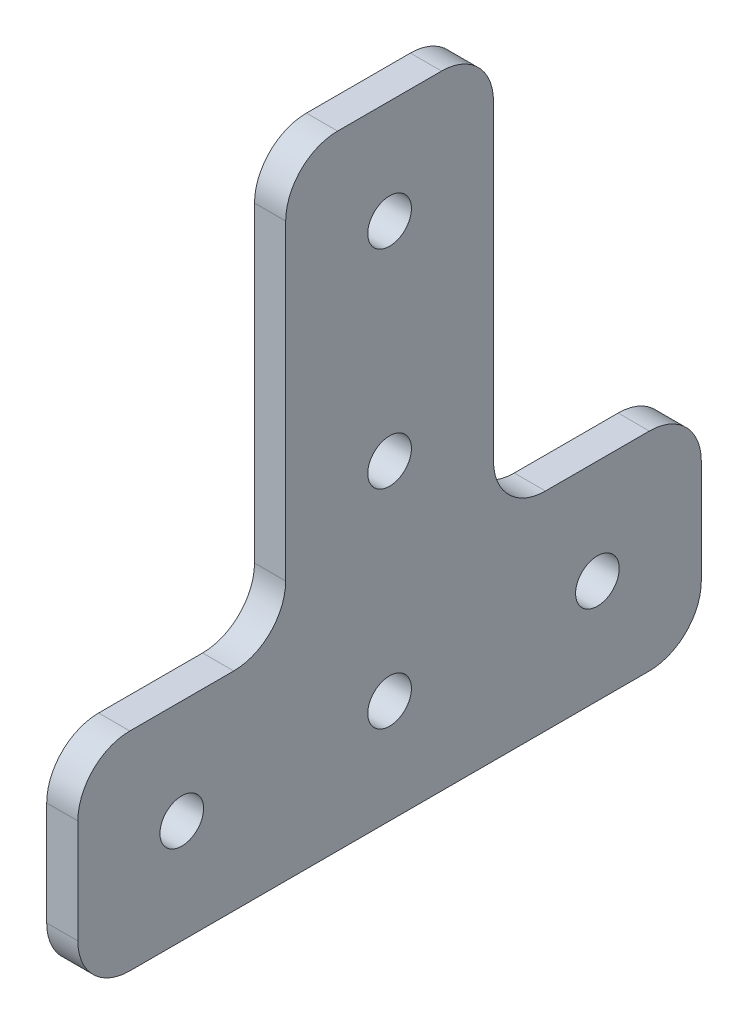
SolidWorks part; units mm, degrees
material "Thornel Mat VMA"
ref_plane "前视基准面" through (0, 0, 0) normal (0, 0, 1) x (1, 0, 0)
ref_plane "上视基准面" through (0, 0, 0) normal (0, 1, 0) x (1, 0, 0)
ref_plane "右视基准面" through (0, 0, 0) normal (1, 0, 0) x (0, 0, -1)
sketch "草图1" plane through (0, 0, 0) normal (1, 0, 0) x (0, 0, -1)
  line L0 (-10, 10) -> (-10, 50)
  line L1 (-30, 10) -> (-10, 10)
  line L2 (-30, 10) -> (-30, -10)
  line L3 (-30, -10) -> (30, -10)
  line L4 (30, 10) -> (30, -10)
  line L5 (-30, 10) -> (30, -10) construction
  line L6 (-30, -10) -> (30, 10) construction
  line L7 (-10, 50) -> (10, 50)
  line L8 (10, 50) -> (10, 10)
  line L9 (10, 10) -> (30, 10)
  circle A0 centre (-20, 0) radius 2.1
  circle A1 centre (0, 0) radius 2.1
  circle A2 centre (20, 0) radius 2.1
  circle A5 centre (0, 20) radius 2.1
  circle A6 centre (0, 40) radius 2.1
  point P0 (0, 0)
  dimension "D5" = 4.2
  dimension "D10" = 4.2
  dimension "D11" = 4.2
  dimension "D1" = 20
  dimension "D2" = 60
  dimension "D3" = 20
  dimension "20" = 20
  dimension "D4" = 40
  dimension "D7" = 20
  dimension "D8" = 20
  dimension "D9" = 20
  dimension "D12" = 10
  dimension "D13" = 10
  dimension "D6" = 3
extrude "凸台-拉伸1" add sketch "草图1" along normal blind 3
fillet "圆角1" radius 5 8 edges at (1.5, 50, 10) (1.5, 50, -10) (1.5, 10, -10) (1.5, 10, -30) (1.5, -10, -30) (1.5, 10, 10) (1.5, 10, 30) (1.5, -10, 30)
